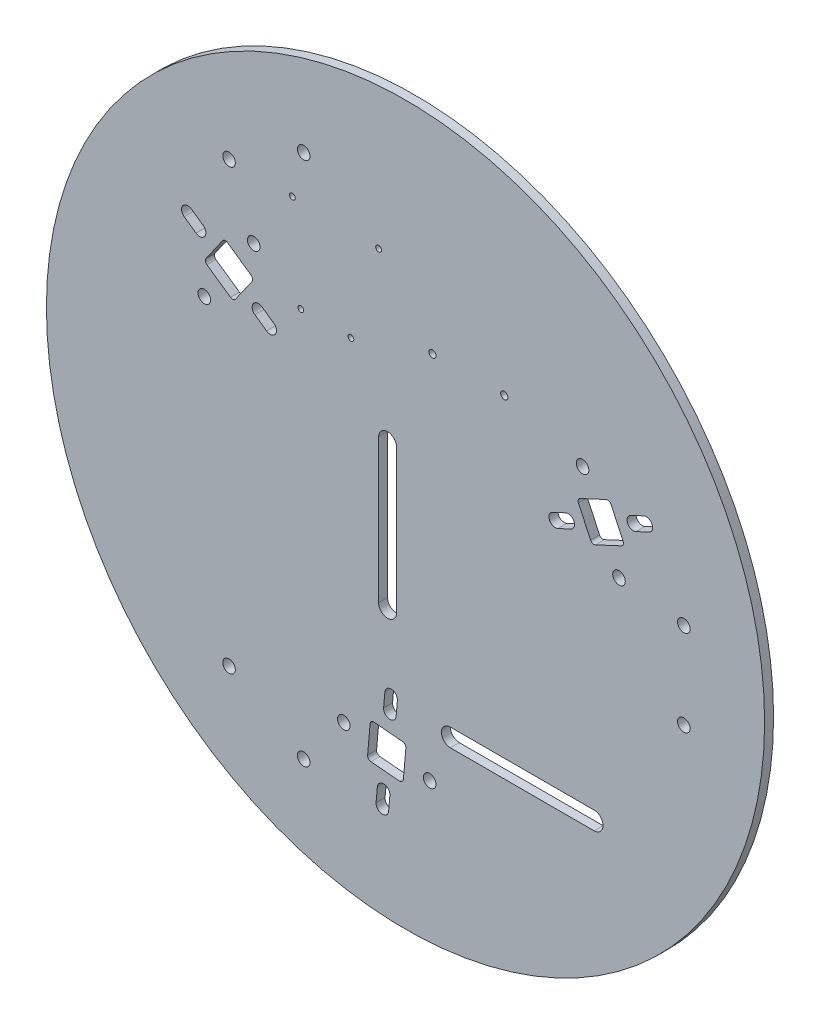
SolidWorks part; units mm, degrees
ref_plane "Front Plane" through (0, 0, 0) normal (0, 0, 1) x (1, 0, 0)
ref_plane "Top Plane" through (0, 0, 0) normal (0, 1, 0) x (1, 0, 0)
ref_plane "Right Plane" through (0, 0, 0) normal (1, 0, 0) x (0, 0, -1)
sketch "Sketch1" plane through (0, 0, 0) normal (0, 0, 1) x (1, 0, 0)
  line L0 (0, 0) -> (-173.2051, 100) construction
  line L1 (0, 0) -> (173.2051, 100) construction
  line L2 (0, 0) -> (0, -200) construction
  line L3 (0, 0) -> (0, 200) construction
  circle A0 centre (0, 0) radius 200
  dimension "D1" = 400
  dimension "D2" = 120
  dimension "D3" = 120
extrude "Boss-Extrude2" add sketch "Sketch1" along normal blind 5
sketch "Sketch9" plane through (0, 0, 5) normal (0, 0, 1) x (1, 0, 0)
  line L0 (0, 0) -> (0, 183.2614) construction
  line L1 (-98.2846, 122.2339) -> (-56.7154, 146.2339) construction
  line L2 (0, 0) -> (-115, 199.1858) construction
  circle A2 centre (-56.7154, 146.2339) radius 3.5
  circle A5 centre (-98.2846, 122.2339) radius 3.5
  point P4 (-77.5, 134.2339)
  dimension "D3" = 7
  dimension "D2" = 24
  dimension "D4" = 155
  dimension "D11" = 30
extrude "Cut-Extrude8" cut sketch "Sketch9" against normal up to surface (5 mm away) up to face at (200, 0, 0)
pattern_circular "CirPattern5" count 3 over 360 about axis through (0, 0, 0) along (0, 0, 1) of "Cut-Extrude8"
sketch "Sketch15" plane through (0, 0, 5) normal (0, 0, 1) x (1, 0, 0)
  line L0 (0, 0) -> (383.7878, 0) construction
  circle A0 centre (15, 85) radius 2
  circle A1 centre (55, 85) radius 2
  dimension "D1" = 4
  dimension "D2" = 4
  dimension "D3" = 40
  dimension "D4" = 85
  dimension "D5" = 15
extrude "Cut-Extrude13" cut sketch "Sketch15" against normal up to surface (5 mm away) up to face at (-53.2154, -146.2339, 0)
sketch "Sketch17" plane through (0, 0, 5) normal (0, 0, 1) x (1, 0, 0)
  line L0 (0, 0) -> (0, 260.2561) construction
  line L1 (0, 0) -> (-189.8731, 132.9506) construction
  line L3 (-112.2255, 66.3734) -> (-95.8425, 54.9019)
  line L5 (-100.754, 82.7565) -> (-84.371, 71.2849)
  line L6 (-112.2255, 66.3734) -> (-100.754, 82.7565)
  line L7 (-95.8425, 54.9019) -> (-84.371, 71.2849)
  line L8 (-81.9152, 57.3576) -> (-75.362, 52.769) construction
  line L9 (-79.9077, 60.2247) -> (-73.3545, 55.6361)
  line L10 (-83.9227, 54.4906) -> (-77.3695, 49.902)
  line L11 (-104.034, 60.6377) -> (-90.1792, 80.4244) construction
  line L12 (-114.6813, 80.3007) -> (-121.2345, 84.8893) construction
  line L13 (-112.6738, 83.1677) -> (-119.227, 87.7563)
  line L14 (-116.6888, 77.4337) -> (-123.242, 82.0223)
  arc A0 (-79.9077, 60.2247) -> (-83.9227, 54.4906) centre (-81.9152, 57.3576) ccw
  arc A1 (-77.3695, 49.902) -> (-73.3545, 55.6361) centre (-75.362, 52.769) ccw
  circle A2 centre (-84.5324, 88.4888) radius 3.5
  circle A3 centre (-112.0641, 49.1695) radius 3.5
  arc A4 (-112.6738, 83.1677) -> (-116.6888, 77.4337) centre (-114.6813, 80.3007) cw
  arc A5 (-123.242, 82.0223) -> (-119.227, 87.7563) centre (-121.2345, 84.8893) cw
  point P7 (-78.6386, 55.0633)
  point P17 (-80.6461, 52.1963)
  point P24 (-117.9579, 82.595)
  dimension "D9" = 7
  dimension "D1" = 20
  dimension "D2" = 20
  dimension "D3" = 20
  dimension "D4" = 55
  dimension "D5" = 110
  dimension "D6" = 7
  dimension "D7" = 8
  dimension "D8" = 10
  dimension "D10" = 14
  dimension "D11" = 10
extrude "Cut-Extrude15" cut sketch "Sketch17" against normal up to surface (5 mm away) up to face at (17, 85, 0)
pattern_circular "CirPattern7" count 3 over 360 about axis through (0, 0, 0) along (0, 0, 1) of "Cut-Extrude15"
sketch "Sketch18" plane through (0, 0, 5) normal (0, 0, 1) x (1, 0, 0)
  line L0 (-10, 30) -> (-10, -50) construction
  line L1 (-5, 30) -> (-5, -50)
  line L2 (-15, 30) -> (-15, -50)
  arc A0 (-5, 30) -> (-15, 30) centre (-10, 30) ccw
  arc A1 (-15, -50) -> (-5, -50) centre (-10, -50) ccw
  point P2 (-10, -10)
  dimension "D1" = 10
  dimension "D2" = 10
  dimension "D3" = 80
  dimension "D4" = 5
extrude "Cut-Extrude16" cut sketch "Sketch18" against normal up to surface (5 mm away) up to face at (-12.5504, -143.452, 0)
sketch "Sketch19" plane through (0, 0, 5) normal (0, 0, 1) x (1, 0, 0)
  line L0 (0, 0) -> (269.2588, 0) construction
  line L1 (25, -95) -> (105, -95) construction
  line L2 (25, -90) -> (105, -90)
  line L3 (25, -100) -> (105, -100)
  arc A0 (25, -90) -> (25, -100) centre (25, -95) ccw
  arc A1 (105, -100) -> (105, -90) centre (105, -95) ccw
  point P5 (65, -95)
  dimension "D1" = 10
  dimension "D2" = 80
  dimension "D3" = 95
  dimension "D4" = 25
extrude "Cut-Extrude17" cut sketch "Sketch19" against normal up to surface (5 mm away) up to face at (-10, -10, 0)
sketch "Sketch20" plane through (0, 0, 5) normal (0, 0, 1) x (1, 0, 0)
  circle A0 centre (-63, 121.9) radius 1.6
  circle A1 centre (-15, 120.8) radius 1.6
  circle A2 centre (-58.3, 70) radius 1.6
  circle A3 centre (-30.4, 70) radius 1.6
  circle A4 centre (15, 85) radius 2 construction
  dimension "D1" = 3.2
  dimension "D2" = 3.2
  dimension "D3" = 3.2
  dimension "D4" = 3.2
  dimension "D5" = 48
  dimension "D6" = 27.9
  dimension "D7" = 4.7
  dimension "D8" = 51.9
  dimension "D9" = 70
  dimension "D10" = 30
  dimension "D11" = 50.8
extrude "Cut-Extrude18" cut sketch "Sketch20" against normal up to surface (5 mm away) up to face at (65, -95, 0)
fillet "Fillet1" radius 2 12 edges at (113.5938, 64.0035, 2.5) (122.0462, 45.8773, 2.5) (95.4677, 55.5511, 2.5) (103.92, 37.4249, 2.5) (-19.5491, -108.7099, 2.5) (-21.2922, -128.6338, 2.5) (0.3748, -110.453, 2.5) (-1.3683, -130.3769, 2.5) (-84.371, 71.2849, 2.5) (-100.754, 82.7565, 2.5) (-112.2255, 66.3734, 2.5) (-95.8425, 54.9019, 2.5)
